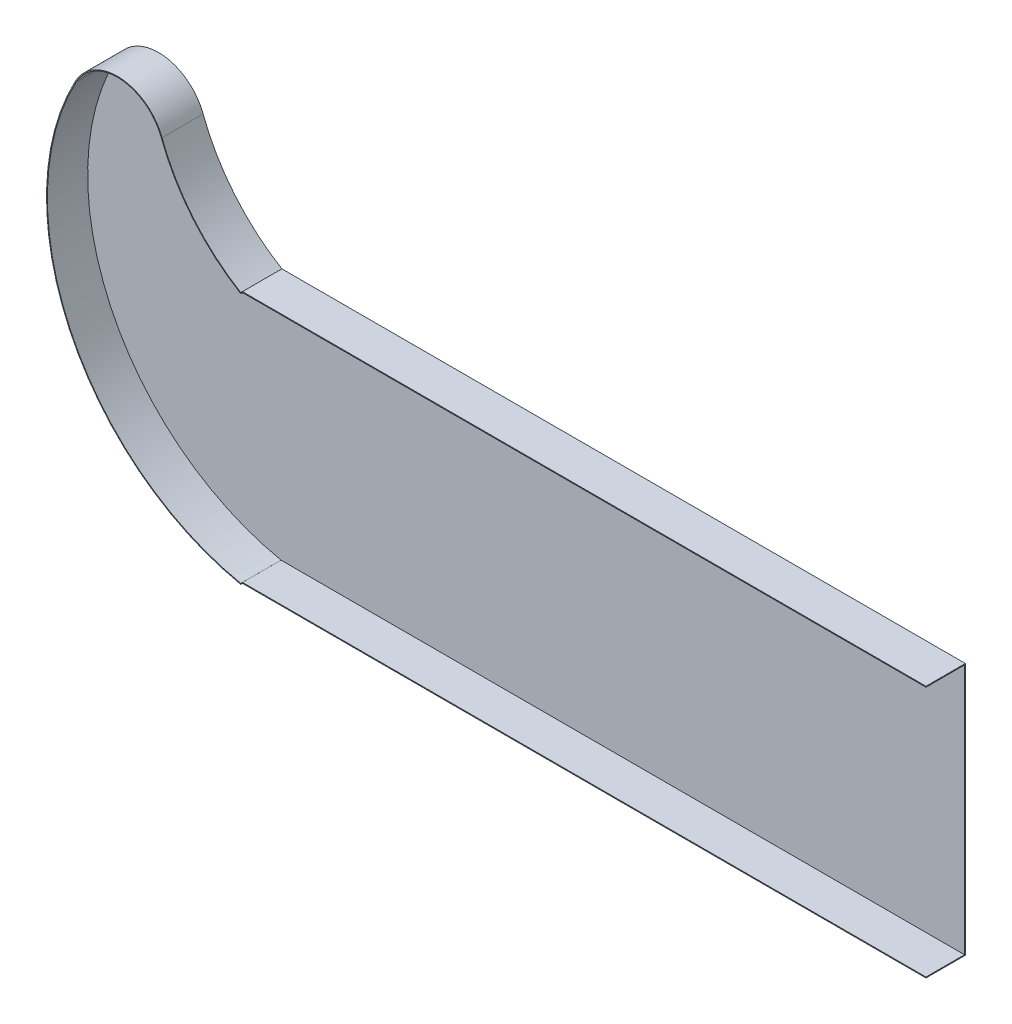
SolidWorks part; units mm, degrees
ref_plane "前视基准面" through (0, 0, 0) normal (0, 0, 1) x (1, 0, 0)
ref_plane "上视基准面" through (0, 0, 0) normal (0, 1, 0) x (1, 0, 0)
ref_plane "右视基准面" through (0, 0, 0) normal (1, 0, 0) x (0, 0, -1)
sketch "草图1" plane through (0, 0, 0) normal (0, 0, 1) x (1, 0, 0)
  line L1 (-798, -295) -> (798, -295)
  line L2 (-798, -295) -> (-798, 295)
  line L3 (-798, 295) -> (798, 295)
  line L4 (798, -295) -> (798, 295)
  line L5 (-798, -295) -> (798, 295) construction
  line L6 (-798, 295) -> (798, -295) construction
  point P0 (0, 0)
  dimension "D1" = 1596
  dimension "D2" = 590
extrude "凸台-拉伸1" add sketch "草图1" along normal blind 2
sketch "草图2" plane through (0, 0, 2) normal (0, 0, 1) x (1, 0, 0)
  line L0 (-798, -293) -> (796, -293)
  line L1 (796, 293) -> (798, 293)
  line L2 (796, 293) -> (-798, 293)
  line L3 (-798, 295) -> (-798, 293)
  line L4 (798, -295) -> (798, 295)
  line L5 (798, 295) -> (-798, 295)
  line L6 (-798, 295) -> (-798, -295)
  line L7 (-798, -295) -> (798, -295)
  line L8 (798, -295) -> (798, 295) construction
  line L9 (798, 295) -> (-798, 295)
  line L10 (-798, -293) -> (-798, -295)
  line L11 (-798, -295) -> (798, -295)
  line L12 (798, 293) -> (798, 295)
  line L13 (796, -293) -> (798, -293)
  line L14 (798, -293) -> (798, -295)
  line L16 (796, -293) -> (796, 293) construction
  line L17 (798, -295) -> (798, 295) construction
  dimension "D1" = 0
  dimension "D2" = 2
extrude "凸台-拉伸2" add sketch "草图2" along normal blind 90
sketch "草图5" plane through (0, 0, 0) normal (0, 0, -1) x (-1, 0, 0)
  line L0 (798, 295) -> (798, -295) construction
  line L1 (798, 295) -> (798, -295)
  arc A0 (1183.9184, 529.9439) -> (798, -295) centre (683.6373, 261.2407) cw
  arc A1 (981.8335, 516.3789) -> (798, 295) centre (571.0984, 670.4369) cw
  arc A2 (1183.9184, 529.9439) -> (981.8335, 516.3789) centre (1085.9526, 477.3261) ccw
  point P4 (962.1031, 449.9346)
  point P10 (0, 0)
  point P11 (1180.7628, 449.9346)
extrude "凸台-拉伸5" add sketch "草图5" against normal blind 96
sketch "草图6" plane through (0, 0, 96) normal (0, 0, 1) x (1, 0, 0)
  line L1 (-798, -295) -> (-798, 295)
  line L2 (-797.9984, 292.6621) -> (-797.5972, -293.041)
  line L3 (-799.0345, 293.2883) -> (-797.9984, 292.6621)
  arc A0 (-983.7061, 515.6765) -> (-799.0345, 293.2883) centre (-571.0984, 670.4369) ccw
  arc A1 (-983.7061, 515.6765) -> (-1182.1564, 528.9975) centre (-1085.9526, 477.3261) ccw
  arc A2 (-1182.1564, 528.9975) -> (-797.5972, -293.041) centre (-683.6373, 261.2407) ccw
  arc A3 (-981.8335, 516.3789) -> (-1183.9184, 529.9439) centre (-1085.9526, 477.3261) ccw
  arc A4 (-1183.9184, 529.9439) -> (-798, -295) centre (-683.6373, 261.2407) ccw
  arc A5 (-981.8335, 516.3789) -> (-798, 295) centre (-571.0984, 670.4369) ccw
  arc A6 (-981.8335, 516.3789) -> (-1183.9184, 529.9439) centre (-1085.9526, 477.3261) ccw construction
  arc A7 (-1183.9184, 529.9439) -> (-798, -295) centre (-683.6373, 261.2407) ccw construction
  arc A8 (-981.8335, 516.3789) -> (-798, 295) centre (-571.0984, 670.4369) ccw construction
  dimension "D1" = 0
  dimension "D2" = 2
extrude "切除-拉伸1" cut sketch "草图6" against normal blind 94
